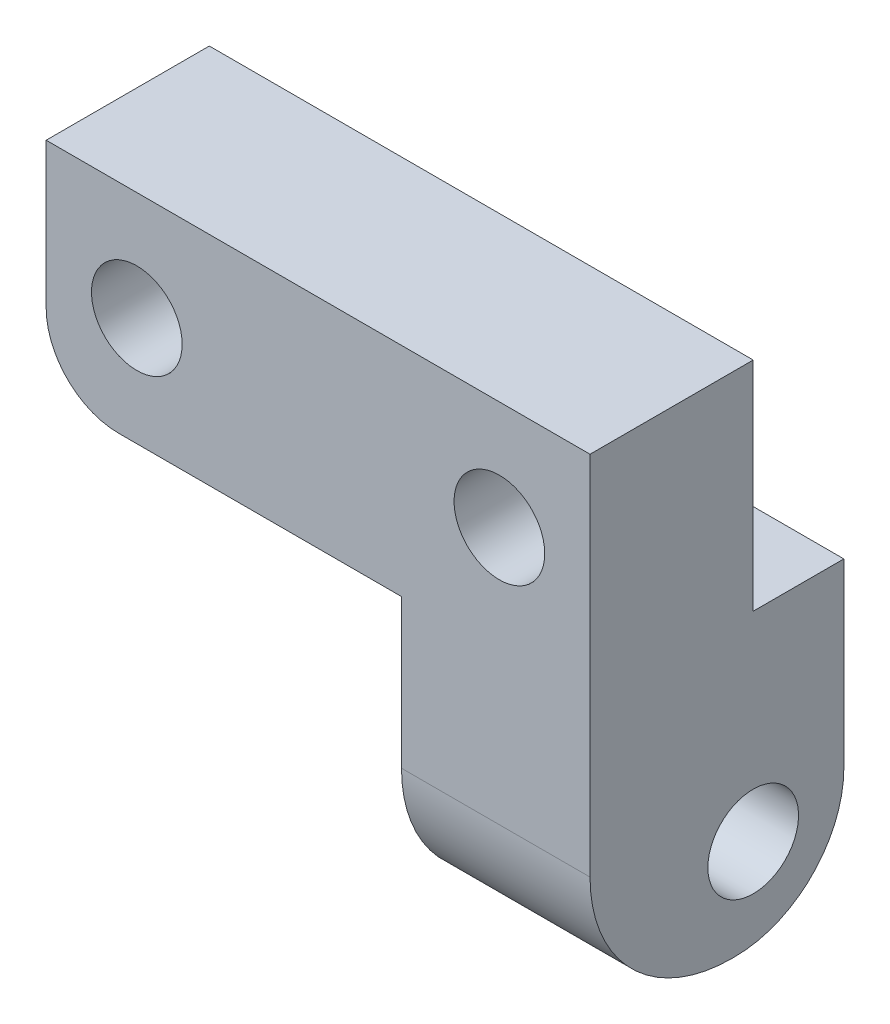
SolidWorks part; units mm, degrees
material "6061 合金"
ref_plane "前视基准面" through (0, 0, 0) normal (0, 0, 1) x (1, 0, 0)
ref_plane "上视基准面" through (0, 0, 0) normal (0, 1, 0) x (1, 0, 0)
ref_plane "右视基准面" through (0, 0, 0) normal (1, 0, 0) x (0, 0, -1)
sketch "草图1" plane through (0, 0, 0) normal (0, 0, 1) x (1, 0, 0)
  line L1 (-7.5, -3) -> (7.5, -3)
  line L2 (-7.5, -3) -> (-7.5, 3)
  line L3 (-7.5, 3) -> (7.5, 3)
  line L4 (7.5, -3) -> (7.5, 3)
  line L5 (0, 3) -> (0, -3) construction
  line L6 (-7.5, 0) -> (7.5, 0) construction
  point P0 (0, 0)
  dimension "D1" = 15
  dimension "D2" = 6
extrude "凸台-拉伸1" add sketch "草图1" along normal blind 4.5
sketch "草图2" plane through (0, 0, 4.5) normal (0, 0, 1) x (1, 0, 0)
  line L0 (-5, 0) -> (5, 0) construction
  point P4 (0, 0)
  dimension "D1" = 10
hole_wizard "M3 螺纹孔1" positions "草图3" profile "草图4" tap size "M3" standard "GB" end condition through all
sketch "草图3" plane through (0, 0, 4.5) normal (0, 0, 1) x (1, 0, 0)
  point P0 (-5, 0)
  point P3 (5, 0)
sketch "草图4" plane through (-5, 0, 4.5) normal (1, 0, 0) x (0, -1, 0)
  line L0 (0, 0) -> (0, 4.5)
  line L1 (0, 4.5) -> (1.25, 4.5)
  line L2 (1.25, 4.5) -> (1.25, 0)
  line L5 (1.25, 0) -> (0, 0)
  line L11 (0, -6.35) -> (0, 107.95) construction
  dimension "通孔螺纹孔钻头直径" = 2.5
  dimension "通孔螺纹孔钻头深度" = 4.5
cosmetic thread "孔螺蚊线1" parameters "D2"=3
cosmetic thread "孔螺蚊线2" parameters "D2"=3
sketch "草图5" plane through (0, 0, 0) normal (1, 0, 0) x (0, 0, -1)
  line L0 (-4.5, -3) -> (-4.5, -11)
  line L1 (-4.5, -11) -> (2.5, -11)
  line L2 (2.5, -11) -> (2.5, -3)
  line L3 (-4.5, -3) -> (0, -3) construction
  line L4 (-4.5, -3) -> (2.5, -3)
  dimension "D1" = 8
  dimension "D2" = 7
extrude "凸台-拉伸2" add sketch "草图5" along normal up to surface (5.2 mm away) from offset 2.3 up to face at (7.5, 0, 2.25)
fillet "圆角1" radius 3.9 1 edges at (4.9, -11, 4.5)
fillet "圆角2" radius 3 1 edges at (4.9, -11, -2.5)
hole_wizard "M3 螺纹孔2" positions "草图7" profile "草图8" tap size "M3" standard "GB" end condition through all
sketch "草图7" plane through (2.3, 0, 0) normal (-1, 0, 0) x (0, 0, 1)
  line L2 (-2.5, -8) -> (-2.5, -3) construction
  line L3 (0.6, -11) -> (0.5, -11) construction
  point P8 (0, -8.5)
  dimension "D1" = 2.5
  dimension "D2" = 2.5
sketch "草图8" plane through (2.3, -8.5, 0) normal (0, 1, 0) x (0, 0, 1)
  line L0 (0, 0) -> (0, 5.2)
  line L1 (0, 5.2) -> (1.25, 5.2)
  line L2 (1.25, 5.2) -> (1.25, 0)
  line L5 (1.25, 0) -> (0, 0)
  line L11 (0, -6.35) -> (0, 107.95) construction
  dimension "通孔螺纹孔钻头直径" = 2.5
  dimension "通孔螺纹孔钻头深度" = 5.2
cosmetic thread "孔螺蚊线3" parameters "D2"=3
fillet "圆角3" radius 2 1 edges at (-7.5, -3, 2.25)
